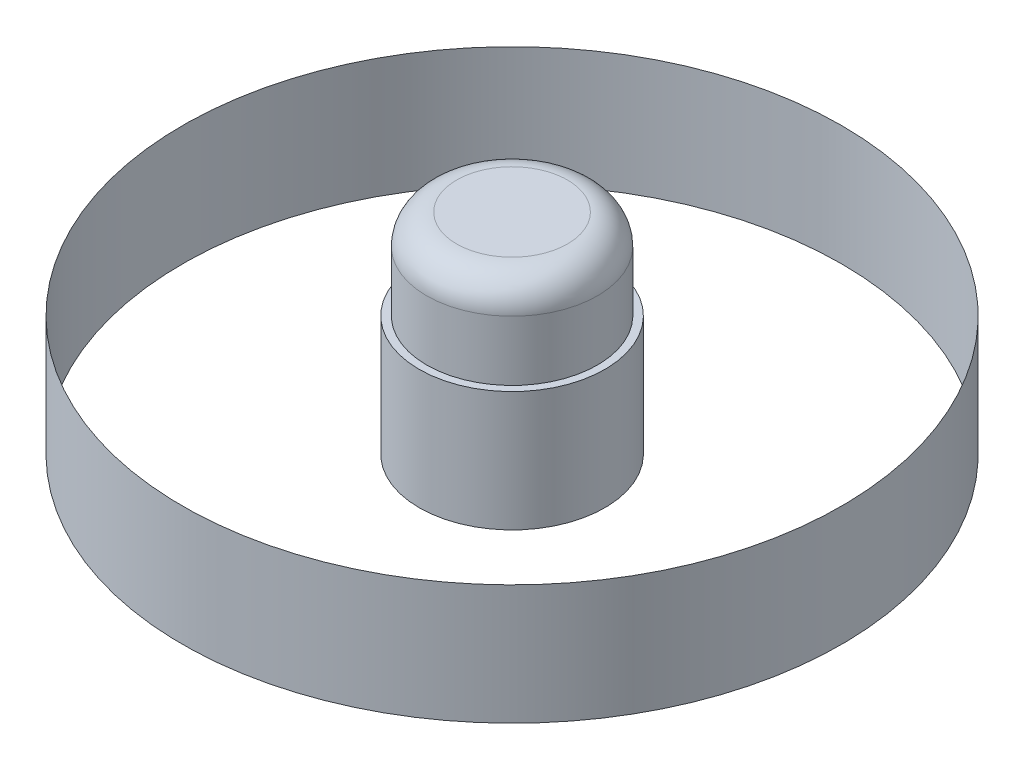
SolidWorks part; units mm, degrees
ref_plane "정면" through (0, 0, 0) normal (0, 0, 1) x (1, 0, 0)
ref_plane "윗면" through (0, 0, 0) normal (0, 1, 0) x (1, 0, 0)
ref_plane "우측면" through (0, 0, 0) normal (1, 0, 0) x (0, 0, -1)
sketch "스케치1" plane through (0, 0, 0) normal (0, 1, 0) x (1, 0, 0)
  circle A0 centre (0, 0) radius 31
  dimension "D1" = 62
extrude "보스-돌출1" add sketch "스케치1" along normal blind 40
sketch "스케치2" plane through (0, 40, 0) normal (0, 1, 0) x (1, 0, 0)
  circle A0 centre (0, 0) radius 28.5
  dimension "D1" = 57
extrude "보스-돌출2" add sketch "스케치2" along normal blind 30
fillet "필렛1" radius 10 1 edges at (0, 70, 28.5)
shell "쉘1" thickness 3
sketch "스케치3" plane through (0, 0, 0) normal (0, -1, 0) x (1, 0, 0)
  circle A0 centre (0, 0) radius 110
  dimension "D1" = 220
surface "곡면-돌출1" sketch "스케치3" parameters "D1"=40
